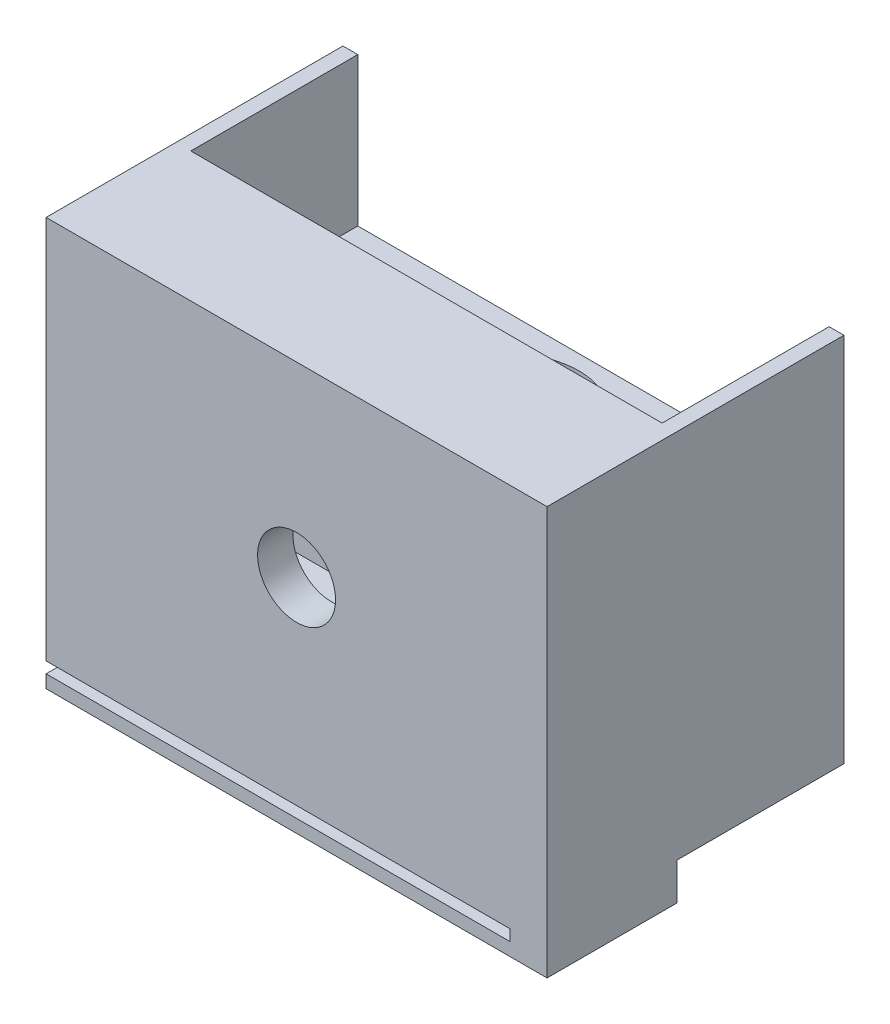
SolidWorks part; units mm, degrees
ref_plane "Front Plane" through (0, 0, 0) normal (0, 0, 1) x (1, 0, 0)
ref_plane "Top Plane" through (0, 0, 0) normal (0, 1, 0) x (1, 0, 0)
ref_plane "Right Plane" through (0, 0, 0) normal (1, 0, 0) x (0, 0, -1)
sketch "Sketch1" plane through (0, 0, 0) normal (0, 1, 0) x (1, 0, 0)
  line L0 (-82.5, 0) -> (52.5, 0) construction
  line L2 (-82.5, 0) -> (-82.5, -35)
  line L4 (-82.5, 0) -> (-82.5, 45)
  line L5 (-82.5, 45) -> (52.5, 45)
  line L6 (52.5, 0) -> (52.5, 45)
  line L7 (-82.5, 0) -> (52.5, 45) construction
  line L8 (-82.5, 45) -> (52.5, 0) construction
  line L9 (-82.5, -35) -> (52.5, -35)
  line L10 (52.5, 0) -> (52.5, -35)
  circle A3 centre (-60, 22.5) radius 13.5
  circle A4 centre (-15, 22.5) radius 18.5
  circle A5 centre (30, 22.5) radius 13.5
  point P4 (0, 0)
  point P8 (0, 0)
extrude "Boss-Extrude1" add sketch "Sketch1" along normal blind 100
sketch "Sketch3" plane through (0, 0, 0) normal (0, -1, 0) x (1, 0, 0)
  line L1 (-32.1587, -40.6818) -> (2.1587, -40.6818)
  line L3 (-32.1587, -4.3182) -> (2.1587, -4.3182)
  line L5 (-35.5803, -36.6933) -> (5.5803, -8.3067) construction
  line L6 (-35.5803, -8.3067) -> (5.5803, -36.6933) construction
  arc A0 (-32.1587, -4.3182) -> (-32.1587, -40.6818) centre (-15, -22.5) ccw
  arc A1 (2.1587, -40.6818) -> (2.1587, -4.3182) centre (-15, -22.5) ccw
extrude "Cut-Extrude1" cut sketch "Sketch3" against normal blind 11.5 contours L3 A1 L1 A0
sketch "Sketch4" plane through (0, 11.5, 0) normal (0, -1, 0) x (1, 0, 0)
  circle A2 centre (-36.25, -22.5) radius 0.7
  circle A3 centre (-30.026, -7.474) radius 0.7
  circle A5 centre (0.026, -7.474) radius 0.7
  circle A6 centre (6.25, -22.5) radius 0.7
  circle A7 centre (0.026, -37.526) radius 0.7
  circle A9 centre (-30.026, -37.526) radius 0.7
  circle A10 centre (-15, -1.25) radius 0.7 [skipped]
  circle A11 centre (-15, -43.75) radius 0.7 [skipped]
  dimension "D1" = 8
extrude "Cut-Extrude2" cut sketch "Sketch4" against normal blind 10
sketch "Sketch5" plane through (0, 100, 0) normal (0, 1, 0) x (1, 0, 0)
  line L3 (-78.5, 0) -> (48.5, 0)
  line L6 (48.5, 47.648) -> (-78.5, 47.648)
  line L7 (-78.5, 47.648) -> (-78.5, 0)
  line L8 (48.5, 47.648) -> (48.5, 0)
extrude "Cut-Extrude3" cut sketch "Sketch5" against normal blind 40
sketch "Sketch6" plane through (-82.5, 0, 0) normal (-1, 0, 0) x (0, 0, 1)
  line L1 (17.5, 85) -> (17.5, 15) construction
  line L8 (9.5, 30) -> (25.5, 30)
  line L9 (9.5, 30) -> (9.5, 70)
  line L10 (9.5, 70) -> (25.5, 70)
  line L11 (25.5, 30) -> (25.5, 70)
  line L12 (9.5, 30) -> (25.5, 70) construction
  line L13 (9.5, 70) -> (25.5, 30) construction
  circle A0 centre (17.5, 85) radius 7.5
  circle A1 centre (17.5, 15) radius 7.5
  point P0 (17.5, 50)
extrude "Cut-Extrude4" cut sketch "Sketch6" against normal blind 92.5
sketch "Sketch10" plane through (0, 0, 35) normal (0, 0, 1) x (1, 0, 0)
  line L0 (-15, 104.3999) -> (-15, -4.932) construction
  line L1 (-88.42, 49.734) -> (67.3314, 49.734) construction
  circle A0 centre (-15, 49.734) radius 10.5
extrude "Cut-Extrude5" cut sketch "Sketch10" against normal up to surface (25.5 mm away) up to face at (-36.25, 50, 9.5)
sketch "Sketch11" plane through (0, 0, 0) normal (0, -1, 0) x (1, 0, 0)
  line L0 (-89.883, 0) -> (65.4693, 0) construction
  line L1 (52.5, 35) -> (52.5, -45) construction
  line L2 (-82.5, 35) -> (52.5, 35)
  line L3 (-82.5, 35) -> (-82.5, 0)
  line L4 (-82.5, 0) -> (52.5, 0)
  line L5 (52.5, 35) -> (52.5, 0)
extrude "Boss-Extrude2" add sketch "Sketch11" along normal blind 10
sketch "Sketch12" plane through (-82.5, 0, 0) normal (-1, 0, 0) x (0, 0, 1)
  line L0 (-52.8258, 0) -> (60.6377, 0) construction
  line L1 (0, 15.453) -> (0, -24.0693) construction
  line L2 (36.0597, -3.5) -> (36.0597, -6.5)
  line L6 (5, -3.5) -> (5, -6.5)
  line L7 (5, -3.5) -> (36.0597, -3.5)
  line L11 (5, -6.5) -> (36.0597, -6.5)
extrude "Cut-Extrude6" cut sketch "Sketch12" against normal blind 125
sketch "Sketch13" plane through (0, -10, 0) normal (0, -1, 0) x (1, 0, 0)
  line L0 (-15, 40.9293) -> (-15, 0) construction
  line L5 (-82.5, 17.5) -> (52.064, 17.5) construction
  line L6 (-82.5, 35) -> (-82.5, 0) construction
  line L7 (-82.5, 0) -> (52.5, 0) construction
  circle A0 centre (-62.5, 17.5) radius 5
  circle A1 centre (32.5, 17.5) radius 5
  circle A2 centre (-15, 17.5) radius 5
  point P0 (-15, 0)
  point P10 (-15, 17.5)
extrude "Cut-Extrude8" cut sketch "Sketch13" against normal blind 10
sketch "Sketch14" plane through (0, -10, 0) normal (0, -1, 0) x (1, 0, 0)
  circle A0 centre (-62.5, 17.5) radius 10
  circle A1 centre (-15, 17.5) radius 10
  circle A2 centre (32.5, 17.5) radius 10
extrude "Cut-Extrude9" cut sketch "Sketch14" against normal blind 2
